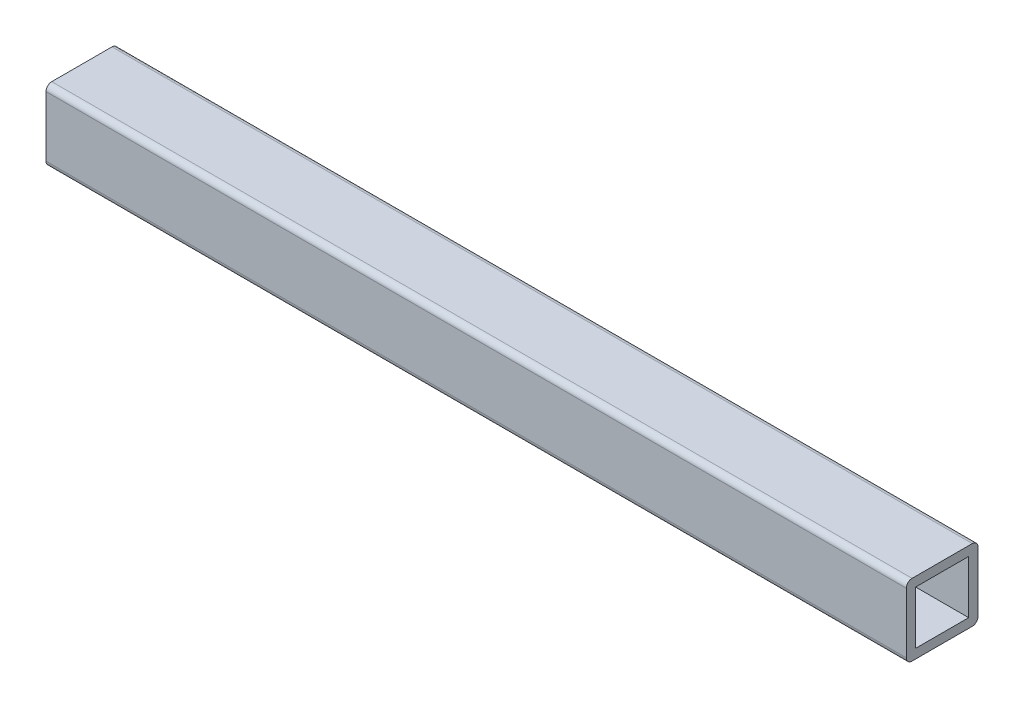
SolidWorks part; units mm, degrees
material "Plain Carbon Steel"
ref_plane "Front Plane" through (0, 0, 0) normal (0, 0, 1) x (1, 0, 0)
ref_plane "Top Plane" through (0, 0, 0) normal (0, 1, 0) x (1, 0, 0)
ref_plane "Right Plane" through (0, 0, 0) normal (1, 0, 0) x (0, 0, -1)
sketch "Sketch1" plane through (0, 0, 0) normal (1, 0, 0) x (0, 0, -1)
  line L0 (0, 2.54) -> (0, 29.21)
  line L1 (-2.54, 31.75) -> (-29.21, 31.75)
  line L2 (-31.75, 29.21) -> (-31.75, 2.54)
  line L3 (-29.21, 0) -> (-2.54, 0)
  line L4 (-4.1275, 4.1275) -> (-4.1275, 27.6225)
  line L5 (-4.1275, 27.6225) -> (-27.6225, 27.6225)
  line L6 (-27.6225, 27.6225) -> (-27.6225, 4.1275)
  line L7 (-27.6225, 4.1275) -> (-4.1275, 4.1275)
  arc A0 (-31.75, 2.54) -> (-29.21, 0) centre (-29.21, 2.54) ccw
  arc A1 (0, 2.54) -> (-2.54, 0) centre (-2.54, 2.54) cw
  arc A2 (0, 29.21) -> (-2.54, 31.75) centre (-2.54, 29.21) ccw
  arc A3 (-31.75, 29.21) -> (-29.21, 31.75) centre (-29.21, 29.21) cw
  arc A4 (-4.1275, 27.6225) -> (-4.1275, 27.6225) centre (-4.1275, 27.6225) ccw
  arc A5 (-27.6225, 27.6225) -> (-27.6225, 27.6225) centre (-27.6225, 27.6225) cw
  arc A6 (-27.6225, 4.1275) -> (-27.6225, 4.1275) centre (-27.6225, 4.1275) ccw
  arc A7 (-4.1275, 4.1275) -> (-4.1275, 4.1275) centre (-4.1275, 4.1275) cw
  point P12 (0, 0)
  point P15 (0, 31.75)
  point P18 (-31.75, 31.75)
  dimension "D3" = 2.54
  dimension "D1" = 31.75
  dimension "D2" = 31.75
  dimension "D4" = 4.1275
extrude "Boss-Extrude1" add sketch "Sketch1" along normal blind 152.4
scale "Scale1" scale about centroid uniform scaling no x scale factor 1 y scale factor 0.4 z scale factor 0.4
